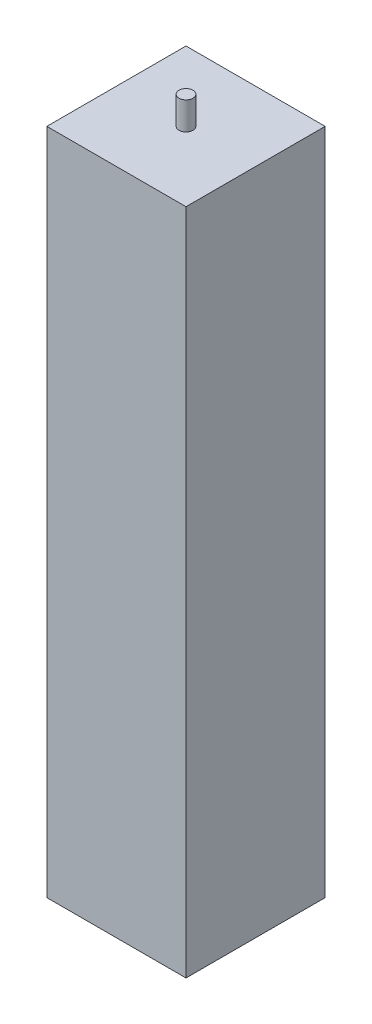
SolidWorks part; units mm, degrees
ref_plane "前视基准面" through (0, 0, 0) normal (0, 0, 1) x (1, 0, 0)
ref_plane "上视基准面" through (0, 0, 0) normal (0, 1, 0) x (1, 0, 0)
ref_plane "右视基准面" through (0, 0, 0) normal (1, 0, 0) x (0, 0, -1)
sketch "草图1" plane through (0, 0, 0) normal (0, 0, 1) x (1, 0, 0)
  line L0 (0, 69.3434) -> (0, -65.7797) construction
  line L1 (-5, 24) -> (5, 24)
  line L2 (-5, 24) -> (-5, -24)
  line L3 (-5, -24) -> (5, -24)
  line L4 (5, 24) -> (5, -24)
  line L5 (37.4584, 0) -> (-19.8575, 0) construction
  dimension "D1" = 48
  dimension "D2" = 10
extrude "凸台-拉伸1" add sketch "草图1" along normal blind 10
sketch "草图2" plane through (0, 24, 0) normal (0, 1, 0) x (1, 0, 0)
  line L0 (0, 2.6031) -> (0, -13.6541) construction
  line L1 (3.5518, -5) -> (-4.1173, -5) construction
  line L2 (5, 0) -> (-5, 0) construction
  line L3 (5, -10) -> (-5, -10) construction
  circle A0 centre (0, -5) radius 0.5
  dimension "D1" = 1
extrude "凸台-拉伸2" add sketch "草图2" along normal blind 2 and the other way blind 49.5
